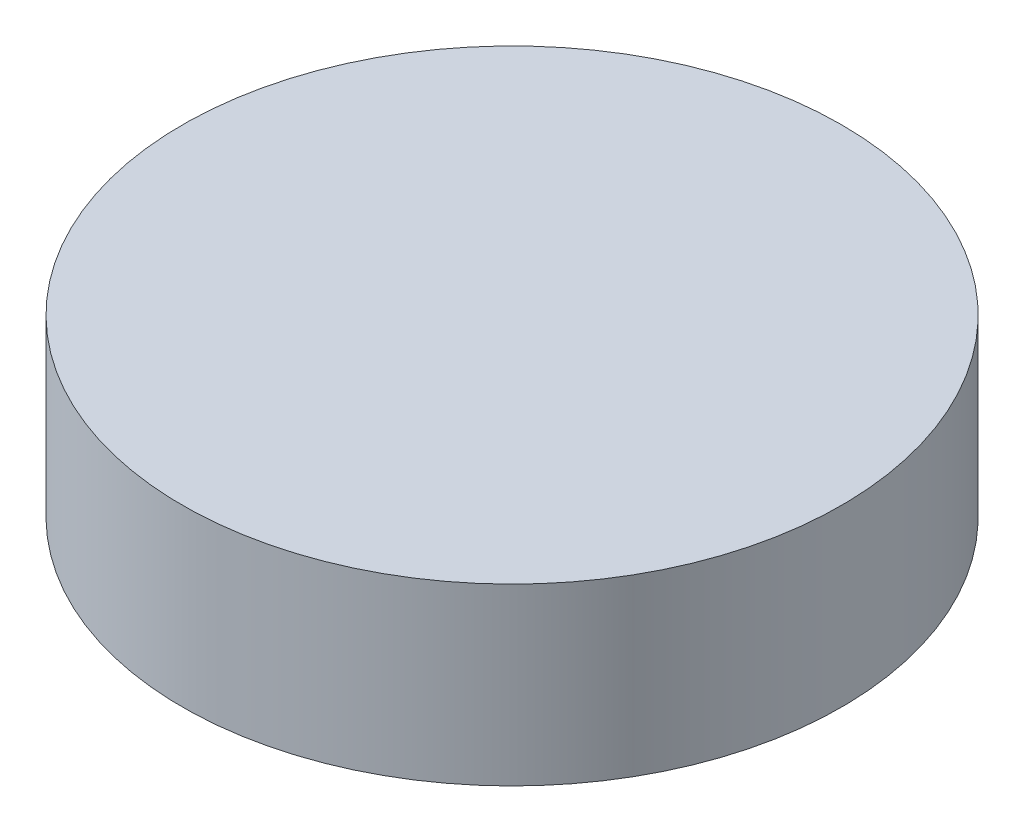
SolidWorks part; units mm, degrees
material "ABS"
ref_plane "Plano frontal" through (0, 0, 0) normal (0, 0, 1) x (1, 0, 0)
ref_plane "Plano superior" through (0, 0, 0) normal (0, 1, 0) x (1, 0, 0)
ref_plane "Plano direito" through (0, 0, 0) normal (1, 0, 0) x (0, 0, -1)
sketch "Esboço1" plane through (0, 0, 0) normal (0, 1, 0) x (1, 0, 0)
  circle A0 centre (0, 0) radius 28.75
  dimension "D1" = 57.5
extrude "Ressalto-extrusão1" add sketch "Esboço1" along normal blind 15.25
shell "Casca1" thickness 3
